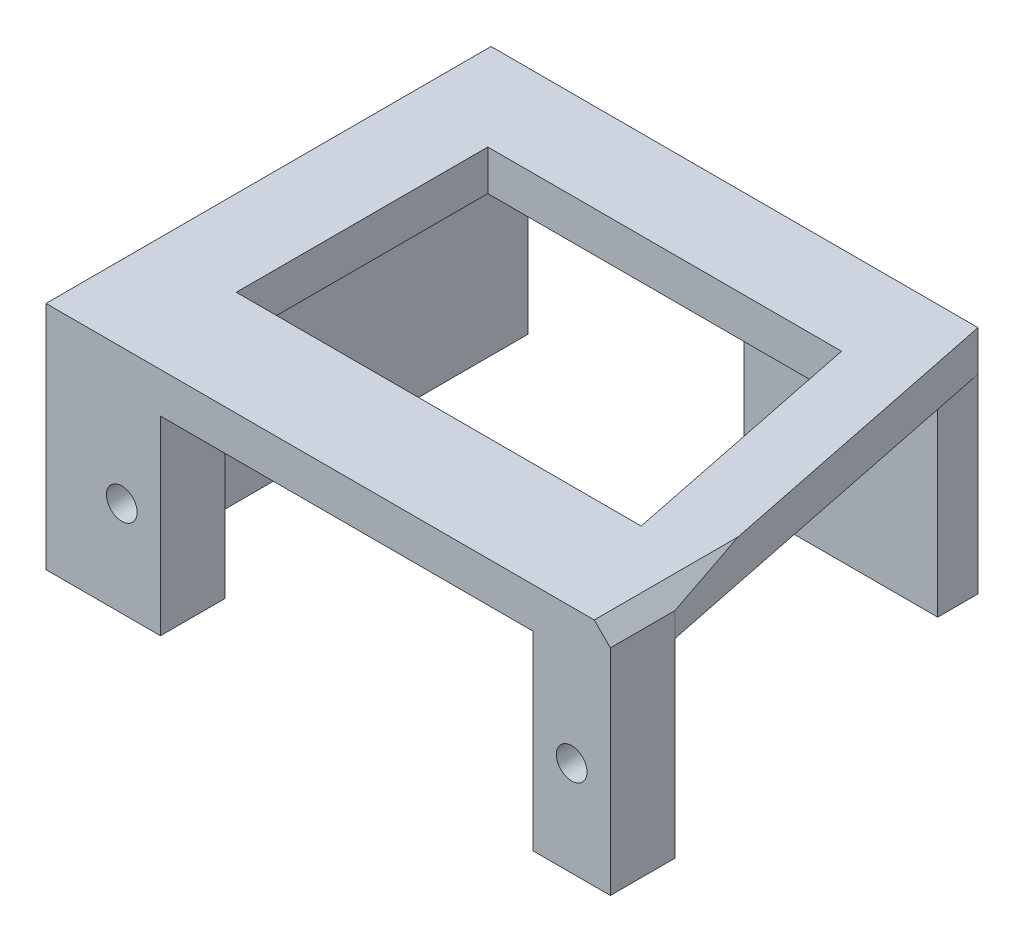
SolidWorks part; units mm, degrees
ref_plane "Front Plane" through (0, 0, 0) normal (0, 0, 1) x (1, 0, 0)
ref_plane "Top Plane" through (0, 0, 0) normal (0, 1, 0) x (1, 0, 0)
ref_plane "Right Plane" through (0, 0, 0) normal (1, 0, 0) x (0, 0, -1)
sketch "Sketch2" plane through (0, 0, 0) normal (0, 1, 0) x (1, 0, 0)
  line L1 (-17.5, -13.8) -> (17.5, -13.8)
  line L2 (-17.5, -13.8) -> (-17.5, 13.8)
  line L3 (-17.5, 13.8) -> (17.5, 13.8)
  line L4 (17.5, -13.8) -> (17.5, 13.8)
  line L5 (-17.5, -13.8) -> (17.5, 13.8) construction
  line L6 (-17.5, 13.8) -> (17.5, -13.8) construction
  point P0 (0, 0)
  dimension "D1" = 35
  dimension "D2" = 27.6
extrude "Boss-Extrude1" add sketch "Sketch2" along normal blind 2.5
sketch "Sketch3" plane through (0, 0, 0) normal (0, -1, 0) x (1, 0, 0)
  line L0 (17.5, -13.8) -> (-17.5, -13.8) construction
  line L1 (0.7, -11.3) -> (12.7, -11.3)
  line L2 (0.7, -11.3) -> (0.7, -13.8)
  line L3 (0.7, -13.8) -> (12.7, -13.8)
  line L4 (12.7, -11.3) -> (12.7, -13.8)
  line L5 (0.7, -11.3) -> (12.7, -13.8) construction
  line L6 (0.7, -13.8) -> (12.7, -11.3) construction
  line L7 (17.5, 13.8) -> (17.5, -13.8) construction
  line L8 (-17.5, 13.8) -> (17.5, 13.8) construction
  line L9 (12.7, 9.8) -> (17.5, 9.8)
  line L10 (12.7, 9.8) -> (12.7, 13.8)
  line L11 (12.7, 13.8) -> (17.5, 13.8)
  line L12 (17.5, 9.8) -> (17.5, 13.8)
  line L13 (12.7, 9.8) -> (17.5, 13.8) construction
  line L14 (12.7, 13.8) -> (17.5, 9.8) construction
  line L16 (-17.5, 13.8) -> (-15.2, 13.8)
  line L17 (-17.5, 13.8) -> (-17.5, -13.8)
  line L18 (-17.5, -13.8) -> (-15.2, -13.8)
  line L19 (-15.2, 9.8) -> (-15.2, -13.8)
  line L20 (-15.2, 13.8) -> (-10.4, 13.8)
  line L22 (-15.2, 9.8) -> (-10.4, 9.8)
  line L23 (-10.4, 13.8) -> (-10.4, 9.8)
  point P0 (6.7, -12.55)
  point P9 (15.1, 11.8)
  dimension "D1" = 4.8
  dimension "D2" = 12
  dimension "D3" = 2.5
  dimension "D4" = 4
  dimension "D5" = 4.8
  dimension "D6" = 32.7
  dimension "D7" = 4.8
extrude "Boss-Extrude2" add sketch "Sketch3" along normal blind 11.8
sketch "Sketch5" plane through (0, 0, -13.8) normal (0, 0, -1) x (-1, 0, 0)
  line L0 (-12.7, -11.8) -> (-12.7, 0) construction
  line L1 (-0.7, -11.8) -> (-12.7, -11.8) construction
  circle A0 centre (-6.7, -6) radius 0.95
  dimension "D3" = 1.9
  dimension "D1" = 6
  dimension "D2" = 5.8
extrude "Cut-Extrude2" cut sketch "Sketch5" against normal blind 11.8
sketch "Sketch6" plane through (0, 0, 9.8) normal (0, 0, -1) x (-1, 0, 0)
  line L0 (-15.1, -11.8) -> (-15.1, 0) construction
  line L1 (-12.7, -11.8) -> (-17.5, -11.8) construction
  line L2 (-12.7, 0) -> (-17.5, 0) construction
  line L3 (-15.1, -11.8) -> (12.8, -11.8) construction
  line L4 (15.2, -11.8) -> (10.4, -11.8) construction
  line L5 (-1.15, -11.8) -> (-1.15, 0) construction
  circle A0 centre (-15.1, -5.9) radius 0.95
  circle A1 centre (12.8, -5.9) radius 0.95
  dimension "D1" = 1.9
extrude "Cut-Extrude3" cut sketch "Sketch6" against normal blind 11.8
sketch "Sketch11" plane through (0, 0, 0) normal (0, -1, 0) x (-1, 0, 0)
  line L0 (-12.7, 13.8) -> (-17.5, -9.8)
  line L1 (-17.5, -9.8) -> (-17.5, 13.8)
  line L2 (-17.5, 13.8) -> (-12.7, 13.8)
  line L3 (-12.9096, -7.3) -> (-9.7367, 8.3)
  line L4 (12.2, 8.3) -> (-12.9096, 8.3) construction
  line L5 (12.2, 8.3) -> (12.2, -7.3) construction
  line L6 (12.2, -7.3) -> (-12.9096, -7.3) construction
  line L7 (-12.9096, 8.3) -> (-12.9096, -7.3) construction
  line L8 (12.2, 8.3) -> (-12.9096, -7.3) construction
  line L9 (12.2, -7.3) -> (-12.9096, 8.3) construction
  line L10 (-9.7367, 8.3) -> (12.2, 8.3)
  line L11 (12.2, 8.3) -> (12.2, -7.3)
  line L12 (12.2, -7.3) -> (-12.9096, -7.3)
  line L13 (15.2, -9.8) -> (10.4, -9.8) construction
  line L14 (15.2, 13.8) -> (15.2, -9.8) construction
  line L15 (-12.7, 11.3) -> (-0.7, 11.3) construction
  point P6 (-0.3548, 0.5)
  dimension "D1" = 2.5
  dimension "D2" = 3
  dimension "D3" = 3
  dimension "D4" = 4
extrude "Cut-Extrude6" cut sketch "Sketch11" against normal blind 10
chamfer "Chamfer1" distance 1 angle 45 1 edges at (17.5, 2.5, 11.8)
